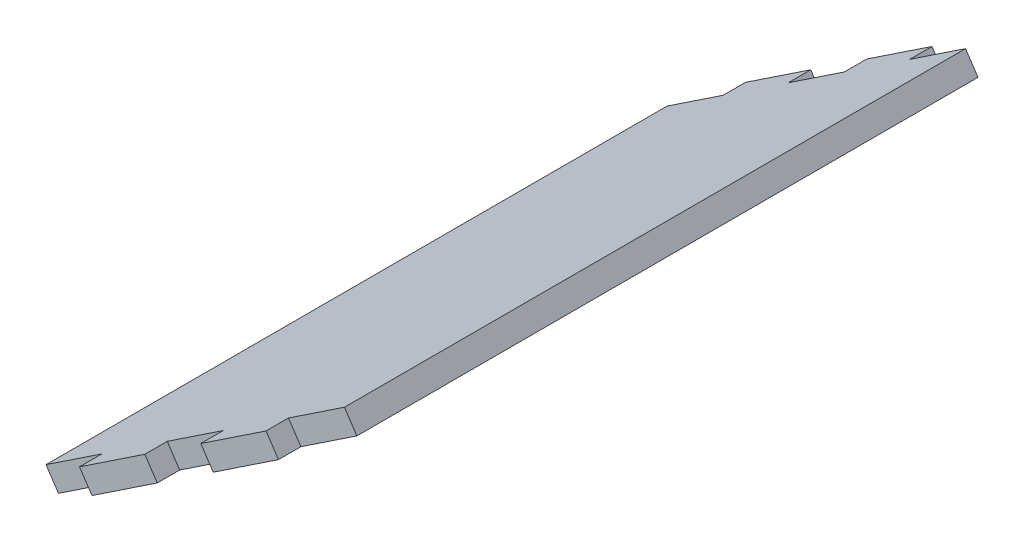
SolidWorks part; units mm, degrees
ref_plane "Front Plane" through (0, 0, 0) normal (0, 0, 1) x (1, 0, 0)
ref_plane "Top Plane" through (0, 0, 0) normal (0, 1, 0) x (1, 0, 0)
ref_plane "Right Plane" through (0, 0, 0) normal (1, 0, 0) x (0, 0, -1)
sketch "Sketch1" plane through (0, 0, 0) normal (0, 0, 1) x (1, 0, 0)
  line L0 (-277.158, 94.6852) -> (-275.3968, 92.0434)
  line L1 (-275.3968, 92.0434) -> (-233.1287, 120.2222)
  line L2 (-233.1287, 120.2222) -> (-234.8898, 122.864)
  line L3 (-234.8898, 122.864) -> (-277.158, 94.6852)
  dimension "D1" = 3.175
  dimension "D2" = 50.8
extrude "Boss-Extrude1" add sketch "Sketch1" against normal up to vertex (94.3225 mm away) contours L1 L2 L3 L0
sketch "Sketch2" plane through (-128.9802, 193.4704, 0) normal (-0.5547, 0.8321, 0) x (0.8321, 0.5547, 0)
  line L0 (-189.1494, 91.1475) -> (-27.571, 91.1475) construction
  line L1 (-178.0875, 94.3225) -> (-168.5625, 94.3225)
  line L2 (-178.0875, 94.3225) -> (-178.0875, 91.1475)
  line L3 (-178.0875, 91.1475) -> (-168.5625, 91.1475)
  line L4 (-168.5625, 94.3225) -> (-168.5625, 91.1475)
  line L5 (-127.2875, 94.3225) -> (-178.0875, 94.3225) construction
  line L6 (-127.2875, 94.3225) -> (-136.8125, 94.3225)
  line L7 (-127.2875, 94.3225) -> (-127.2875, 91.1475)
  line L8 (-127.2875, 91.1475) -> (-136.8125, 91.1475)
  line L9 (-136.8125, 94.3225) -> (-136.8125, 91.1475)
  line L10 (-157.45, 94.3225) -> (-147.925, 94.3225)
  line L11 (-157.45, 94.3225) -> (-157.45, 91.1475)
  line L12 (-157.45, 91.1475) -> (-147.925, 91.1475)
  line L13 (-147.925, 94.3225) -> (-147.925, 91.1475)
  line L14 (-27.571, 3.175) -> (-189.1494, 3.175) construction
  line L15 (-178.0875, 0) -> (-168.5625, 0)
  line L16 (-178.0875, 0) -> (-178.0875, 3.175)
  line L17 (-178.0875, 3.175) -> (-168.5625, 3.175)
  line L18 (-168.5625, 0) -> (-168.5625, 3.175)
  line L19 (-127.2875, 0) -> (-178.0875, 0) construction
  line L20 (-127.2875, 0) -> (-136.8125, 0)
  line L21 (-127.2875, 0) -> (-127.2875, 3.175)
  line L22 (-127.2875, 3.175) -> (-136.8125, 3.175)
  line L23 (-136.8125, 0) -> (-136.8125, 3.175)
  line L24 (-147.925, 0) -> (-157.45, 0)
  line L25 (-147.925, 0) -> (-147.925, 3.175)
  line L26 (-147.925, 3.175) -> (-157.45, 3.175)
  line L27 (-157.45, 0) -> (-157.45, 3.175)
  dimension "D1" = 9.525
  dimension "D2" = 9.525
  dimension "D3" = 9.525
  dimension "D4" = 11.1125
  dimension "D5" = 9.525
  dimension "D6" = 9.525
  dimension "D7" = 9.525
  dimension "D8" = 11.1125
extrude "Cut-Extrude1" cut sketch "Sketch2" against normal through all
